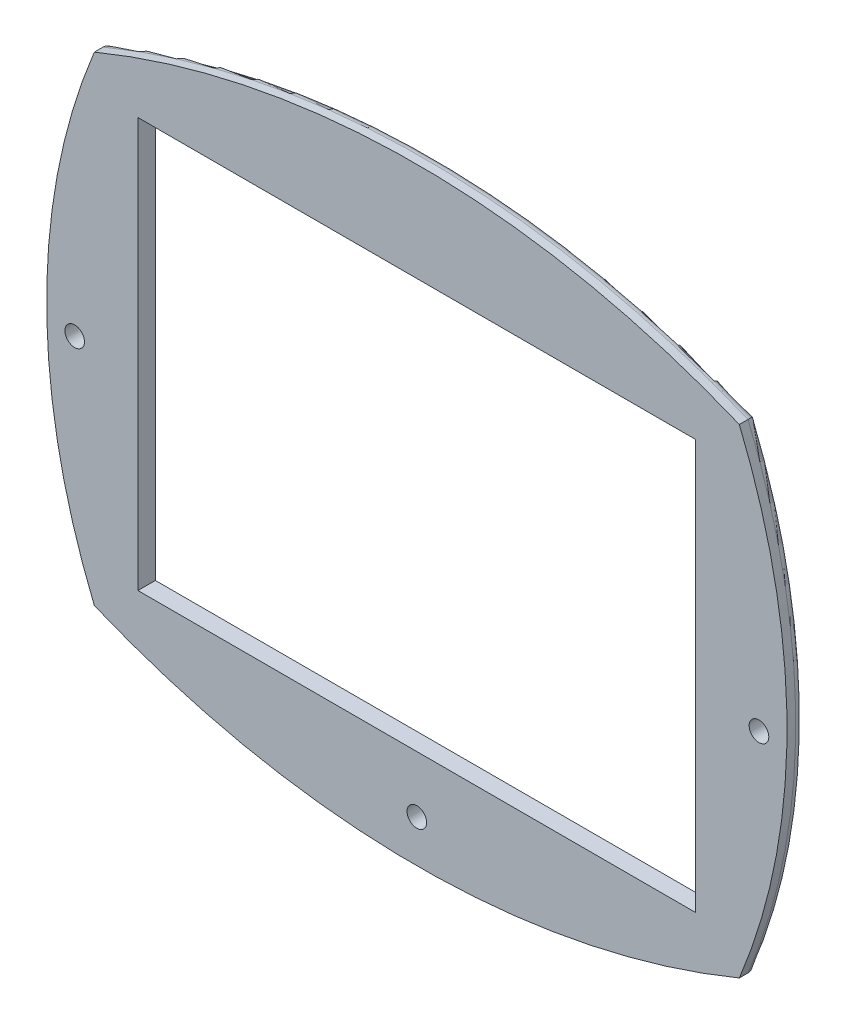
SolidWorks part; units mm, degrees
ref_plane "Front Plane" through (0, 0, 0) normal (0, 0, 1) x (1, 0, 0)
ref_plane "Top Plane" through (0, 0, 0) normal (0, 1, 0) x (1, 0, 0)
ref_plane "Right Plane" through (0, 0, 0) normal (1, 0, 0) x (0, 0, -1)
sketch "Sketch1" plane through (0, 0, 0) normal (0, 0, 1) x (1, 0, 0)
  line L1 (0, 34.8598) -> (0, -34.8598) construction
  line L2 (-32, 23.5) -> (32, 23.5)
  line L3 (-32, 23.5) -> (-32, -23.5)
  line L4 (-32, -23.5) -> (32, -23.5)
  line L5 (32, 23.5) -> (32, -23.5)
  line L6 (-32, 23.5) -> (32, -23.5) construction
  line L7 (-32, -23.5) -> (32, 23.5) construction
  arc A0 (-37, 27.5) -> (37, 27.5) centre (0, -61.8259) cw
  arc A1 (-37, 27.5) -> (-37, -27.5) centre (29.3909, 0) ccw
  arc A2 (-37, -27.5) -> (37, -27.5) centre (0, 61.8259) ccw
  arc A3 (37, 27.5) -> (37, -27.5) centre (-29.3909, 0) cw
  arc A4 (36, -25.5) -> (-36, -25.5) centre (0, 65.6482) cw
  arc A5 (-36, 25.5) -> (-36, -25.5) centre (34.5319, 0) ccw
  arc A6 (-36, 25.5) -> (36, 25.5) centre (0, -65.6482) cw
  arc A7 (36, -25.5) -> (36, 25.5) centre (-34.5319, 0) ccw
  point P1 (-37, -27.5)
  point P2 (37, -27.5)
  point P3 (-37, 27.5)
  point P4 (37, 27.5)
  point P5 (0, 0)
  point P15 (-42.4701, 0)
  point P16 (42.4701, 0)
  point P17 (0, -34.8598)
  point P18 (0, 34.8598)
  point P19 (0, 0)
  dimension "D5" = 47
  dimension "D1" = 72
  dimension "D2" = 51
  dimension "D3" = 55
  dimension "D4" = 74
  dimension "D6" = 64
extrude "Boss-Extrude1" add sketch "Sketch1" along normal blind 2 contours A4 A7 A6 A5 L2 L5 L4 L3 | A3 A0 A1 A2 A7 A4 A5 A6
fillet "Fillet1" radius 1 4 edges at (-42.4701, 0, 0) (0, -34.8598, 0) (42.4701, 0, 0) (0, 34.8598, 0)
sketch "Sketch2" plane through (0, 0, 0) normal (0, 0, -1) x (-1, 0, 0)
  circle A0 centre (-39.2539, -1.86) radius 1.125
  circle A1 centre (0, -30) radius 1.125
  circle A2 centre (39.2539, -1.86) radius 1.125
  arc A5 (37, -27.5) -> (37, 27.5) centre (-29.3909, 0) ccw construction
  arc A6 (-37, 27.5) -> (-37, -27.5) centre (29.3909, 0) ccw construction
  arc A7 (-37, -27.5) -> (37, -27.5) centre (0, 61.8259) ccw construction
  dimension "D1" = 68.67
  dimension "D3" = 2.25
  dimension "D4" = 2.25
  dimension "D5" = 2.25
  dimension "D2" = 68.67
  dimension "D6" = 37
  dimension "D7" = 91.8259
  dimension "D8" = 25.64
  dimension "D9" = 25.64
extrude "Cut-Extrude1" cut sketch "Sketch2" against normal through all
